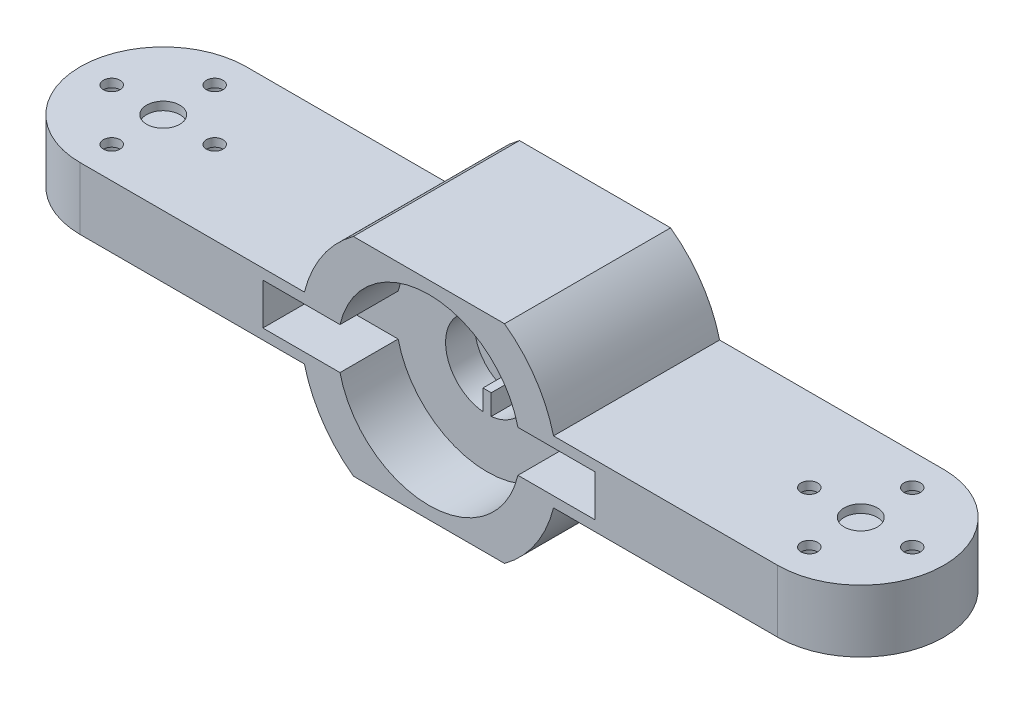
SolidWorks part; units mm, degrees
material "6061 Alloy"
ref_plane "Front Plane" through (0, 0, 0) normal (0, 0, 1) x (1, 0, 0)
ref_plane "Top Plane" through (0, 0, 0) normal (0, 1, 0) x (1, 0, 0)
ref_plane "Right Plane" through (0, 0, 0) normal (1, 0, 0) x (0, 0, -1)
sketch "Sketch1" plane through (0, 0, 0) normal (0, 1, 0) x (1, 0, 0)
  line L1 (-42, -10) -> (42, -10)
  line L3 (-42, 10) -> (42, 10)
  line L5 (-42, -10) -> (42, 10) construction
  line L6 (-42, 10) -> (42, -10) construction
  arc A0 (-42, 10) -> (-42, -10) centre (-42, 0) ccw
  arc A1 (42, -10) -> (42, 10) centre (42, 0) ccw
  point P0 (0, 0)
  point P7 (52, 0)
  dimension "D3" = 10
  dimension "D1" = 84
  dimension "D2" = 20
  dimension "D4" = 10
extrude "Boss-Extrude1" add sketch "Sketch1" along normal blind 25
sketch "Sketch2" plane through (0, 0, 10) normal (0, 0, 1) x (1, 0, 0)
  line L0 (0, 0) -> (0, 12.5) construction
  circle A0 centre (0, 12.5) radius 11
  dimension "D2" = 22
  dimension "D1" = 12.5
extrude "Cut-Extrude1" cut sketch "Sketch2" against normal blind 7
sketch "Sketch3" plane through (0, 0, 0) normal (0, -1, 0) x (1, 0, 0)
  line L0 (-42, 10) -> (42, 10) construction
  line L2 (15, -10) -> (15, 10)
  line L4 (-15, -10) -> (-15, 10)
  line L5 (15, -10) -> (-15, 10) construction
  line L6 (15, 10) -> (-15, -10) construction
  line L7 (-15, 10) -> (-42, 10)
  line L8 (-42, -10) -> (-15, -10)
  line L9 (15, 10) -> (42, 10)
  line L10 (15, -10) -> (42, -10)
  arc A0 (-42, 10) -> (-42, -10) centre (-42, 0) ccw
  arc A1 (42, -10) -> (42, 10) centre (42, 0) ccw
  point P7 (0, 0)
extrude "Cut-Extrude3" cut sketch "Sketch3" against normal blind 8.75
sketch "Sketch4" plane through (0, 25, 0) normal (0, 1, 0) x (1, 0, 0)
  line L0 (15, -10) -> (15, 10)
  line L1 (-15, -10) -> (-15, 10)
  line L2 (15, -10) -> (-15, 10) construction
  line L3 (15, 10) -> (-15, -10) construction
  line L4 (-15, 10) -> (-55, 10)
  line L5 (-55, -10) -> (-15, -10)
  line L6 (15, 10) -> (55, 10)
  line L7 (15, -10) -> (55, -10)
  arc A0 (-55, 10) -> (-55, -10) centre (-55, 0) ccw
  arc A1 (55, -10) -> (55, 10) centre (55, 0) ccw
  point P2 (0, 0)
  dimension "D1" = 0
  dimension "D2" = 0
extrude "Cut-Extrude5" cut sketch "Sketch4" against normal blind 8.75
sketch "Sketch5" plane through (0, 16.25, 0) normal (0, 1, 0) x (1, 0, 0)
  line L0 (0, 0) -> (-42, 0) construction
  line L1 (-42, 0) -> (-35.8, 0) construction
  line L2 (-42, 0) -> (-42, 6.2) construction
  line L3 (-42, 0) -> (-48.2, 0) construction
  line L4 (-42, 0) -> (-42, -6.2) construction
  line L5 (0, 0) -> (42, 0) construction
  line L6 (42, 0) -> (48.2, 0) construction
  line L7 (42, 0) -> (42, 6.2) construction
  line L8 (42, 0) -> (35.8, 0) construction
  line L9 (42, 0) -> (42, -6.2) construction
  circle A0 centre (-42, 6.2) radius 1
  circle A1 centre (-35.8, 0) radius 1
  circle A2 centre (-42, -6.2) radius 1
  circle A3 centre (-48.2, 0) radius 1
  circle A4 centre (42, 6.2) radius 1
  circle A5 centre (48.2, 0) radius 1
  circle A6 centre (42, -6.2) radius 1
  circle A7 centre (35.8, 0) radius 1
  dimension "D3" = 2
  dimension "D4" = 2
  dimension "D5" = 2
  dimension "D6" = 2
  dimension "D13" = 2
  dimension "D14" = 2
  dimension "D15" = 2
  dimension "D16" = 2
  dimension "D1" = 6.2
  dimension "D2" = 6.2
  dimension "D7" = 6.2
  dimension "D8" = 6.2
  dimension "D9" = 0
  dimension "D10" = 0
  dimension "D11" = 6.2
  dimension "D12" = 6.2
  dimension "D17" = 6.2
  dimension "D18" = 6.2
  dimension "D19" = 0
  dimension "D20" = 0
extrude "Cut-Extrude6" cut sketch "Sketch5" against normal blind 7.5
sketch "Sketch6" plane through (0, 8.75, 0) normal (0, -1, 0) x (1, 0, 0)
  line L0 (0, 0) -> (-42, 0) construction
  line L1 (-42, 0) -> (-35.8, 0) construction
  line L2 (-42, 0) -> (-48.2, 0) construction
  line L3 (-42, 0) -> (-42, 6.2) construction
  line L4 (-42, 0) -> (-42, -6.2) construction
  line L5 (-48.2, 0) -> (-35.8, 0) construction
  line L6 (0, 0) -> (42, 0) construction
  line L7 (42, 0) -> (48.2, 0) construction
  line L8 (42, 0) -> (35.8, 0) construction
  line L9 (42, 0) -> (42, 6.2) construction
  line L10 (42, 0) -> (42, -6.2) construction
  line L11 (35.8, 0) -> (48.2, 0) construction
  circle A0 centre (-42, 6.2) radius 1.95
  circle A1 centre (-35.8, 0) radius 1.95
  circle A2 centre (-48.2, 0) radius 1.95
  circle A3 centre (-42, -6.2) radius 1.95
  circle A4 centre (42, 6.2) radius 1.95
  circle A5 centre (48.2, 0) radius 1.95
  circle A6 centre (35.8, 0) radius 1.95
  circle A7 centre (42, -6.2) radius 1.95
  dimension "D5" = 3.9
  dimension "D6" = 3.9
  dimension "D7" = 3.9
  dimension "D8" = 3.9
  dimension "D15" = 3.9
  dimension "D16" = 3.9
  dimension "D17" = 3.9
  dimension "D18" = 3.9
  dimension "D1" = 6.2
  dimension "D2" = 6.2
  dimension "D3" = 6.2
  dimension "D4" = 6.2
  dimension "D9" = 0
  dimension "D10" = 0
  dimension "D11" = 6.2
  dimension "D12" = 6.2
  dimension "D13" = 6.2
  dimension "D14" = 6.2
  dimension "D19" = 0
  dimension "D20" = 0
  dimension "D21" = 42
extrude "Cut-Extrude7" cut sketch "Sketch6" against normal offset from surface (6.5 mm away) 1 up to face at (-42, 16.25, -5.2)
sketch "Sketch7" plane through (0, 16.25, 0) normal (0, 1, 0) x (1, 0, 0)
  line L0 (0, 0) -> (-42, 0) construction
  line L1 (0, 0) -> (42, 0) construction
  circle A0 centre (-42, 0) radius 2
  circle A1 centre (42, 0) radius 2
  dimension "D1" = 4
  dimension "D2" = 4
extrude "Cut-Extrude8" cut sketch "Sketch7" against normal blind 1
sketch "Sketch8" plane through (0, 0, 10) normal (0, 0, 1) x (1, 0, 0)
  line L0 (0, 0) -> (0, 12.5) construction
  line L1 (-15, 16.25) -> (-15, 25)
  line L2 (15, 0) -> (9.1001, 0)
  line L3 (15, 0) -> (15, 8.75)
  line L4 (15, 25) -> (9.1001, 25)
  line L5 (-15, 0) -> (-15, 8.75)
  line L6 (15, 0) -> (-15, 25) construction
  line L7 (15, 25) -> (-15, 0) construction
  line L8 (-9.1001, 25) -> (-15, 25)
  line L9 (15, 16.25) -> (15, 25)
  line L10 (-9.1001, 0) -> (-15, 0)
  arc A0 (-15, 8.75) -> (-9.1001, 0) centre (0, 12.5) ccw
  arc A1 (-9.1001, 25) -> (-15, 16.25) centre (0, 12.5) ccw
  arc A2 (15, 16.25) -> (9.1001, 25) centre (0, 12.5) ccw
  arc A3 (9.1001, 0) -> (15, 8.75) centre (0, 12.5) ccw
  dimension "D1" = 12.5
extrude "Cut-Extrude9" cut sketch "Sketch8" against normal through all
sketch "Sketch9" plane through (0, 0, 3) normal (0, 0, 1) x (1, 0, 0)
  line L0 (0, 0) -> (0, 12.5) construction
  line L2 (-0.5, 10) -> (0.5, 10)
  line L4 (-0.5, 15) -> (0.5, 15)
  line L6 (-0.5, 10) -> (0.5, 15) construction
  line L7 (-0.5, 15) -> (0.5, 10) construction
  line L8 (0.5, 15) -> (-0.5, 15)
  line L9 (0.5, 15) -> (0.5, 17.4749)
  line L11 (-0.5, 15) -> (-0.5, 17.4749)
  line L12 (0.5, 10) -> (-0.5, 10)
  line L13 (0.5, 10) -> (0.5, 7.5251)
  line L15 (-0.5, 10) -> (-0.5, 7.5251)
  arc A0 (-0.5, 17.4749) -> (-0.5, 7.5251) centre (0, 12.5) ccw
  arc A1 (0.5, 7.5251) -> (0.5, 17.4749) centre (0, 12.5) ccw
  dimension "D1" = 5
  dimension "D3" = 10
  dimension "D2" = 1
  dimension "D4" = 1
  dimension "D5" = 2.4749
extrude "Cut-Extrude10" cut sketch "Sketch9" against normal blind 3.5 contours L13 A1 L9 L4 L11 A0 L15 L2
sketch "Sketch10" plane through (0, 0, 10) normal (0, 0, 1) x (1, 0, 0)
  line L1 (-20, 15) -> (20, 15)
  line L2 (-20, 15) -> (-20, 10)
  line L3 (-20, 10) -> (20, 10)
  line L4 (20, 15) -> (20, 10)
  line L5 (-20, 15) -> (20, 10) construction
  line L6 (-20, 10) -> (20, 15) construction
  point P0 (0, 12.5)
  dimension "D1" = 5
  dimension "D2" = 40
extrude "Cut-Extrude11" cut sketch "Sketch10" against normal blind 7
